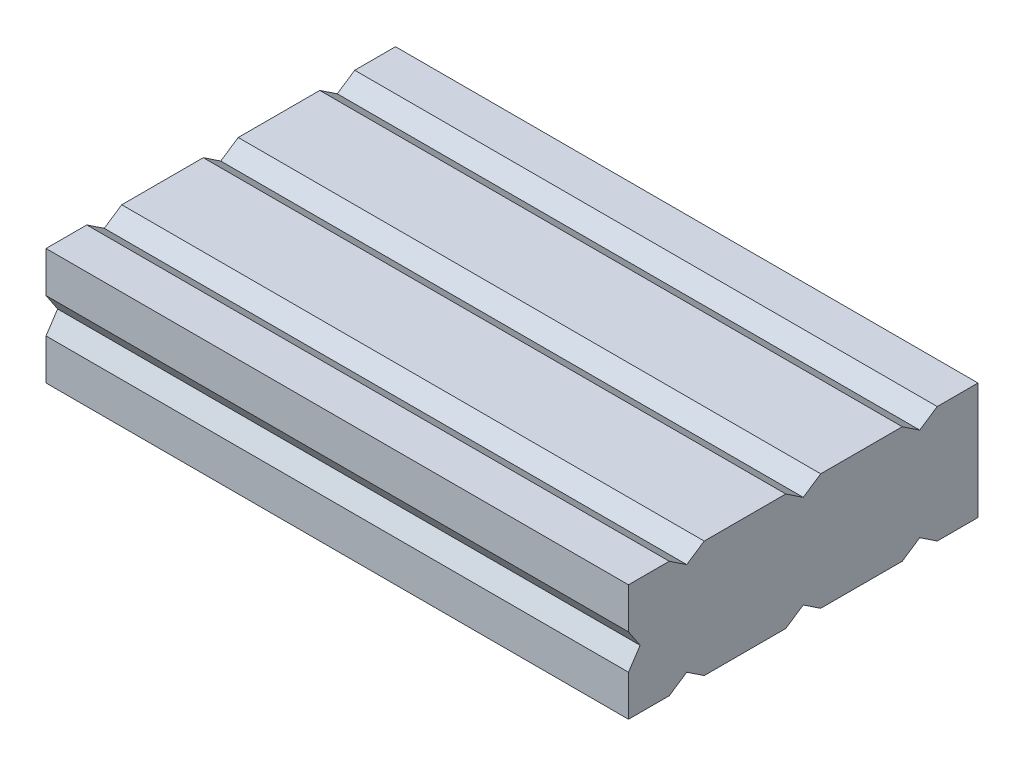
SolidWorks part; units mm, degrees
ref_plane "Front" through (0, 0, 0) normal (0, 0, 1) x (1, 0, 0)
ref_plane "Top" through (0, 0, 0) normal (0, 1, 0) x (1, 0, 0)
ref_plane "Right" through (0, 0, 0) normal (1, 0, 0) x (0, 0, -1)
sketch "Skizze1" plane through (0, 0, 0) normal (1, 0, 0) x (0, 0, -1)
  line L0 (-30, 10) -> (-30, -10) construction
  line L1 (-40, -10) -> (-33, -10)
  line L2 (-40, -10) -> (-40, -3)
  line L3 (-40, 10) -> (-33, 10)
  line L4 (40, -10) -> (40, -3)
  line L5 (-40, -10) -> (40, 10) construction
  line L6 (-40, 10) -> (40, -10) construction
  line L7 (-33, 10) -> (-30, 8)
  line L8 (-27, 10) -> (-30, 8)
  line L9 (0, 0) -> (-40, 0) construction
  line L10 (-7, 10) -> (-10, 8)
  line L11 (-13, 10) -> (-10, 8)
  line L12 (13, 10) -> (10, 8)
  line L13 (7, 10) -> (10, 8)
  line L14 (33, 10) -> (30, 8)
  line L15 (27, 10) -> (30, 8)
  line L16 (33, -10) -> (30, -8)
  line L17 (27, -10) -> (30, -8)
  line L18 (13, -10) -> (10, -8)
  line L19 (7, -10) -> (10, -8)
  line L20 (-7, -10) -> (-10, -8)
  line L21 (-13, -10) -> (-10, -8)
  line L22 (-33, -10) -> (-30, -8)
  line L23 (-27, -10) -> (-30, -8)
  line L24 (-40, 3) -> (-38, 0)
  line L25 (-40, -3) -> (-38, 0)
  line L26 (0, 0) -> (0, 10) construction
  line L27 (40, -3) -> (38, 0)
  line L28 (40, 3) -> (38, 0)
  line L29 (-30, 10) -> (-27, 10) construction
  line L30 (-27, 10) -> (-13, 10)
  line L31 (-33, 10) -> (-30, 10) construction
  line L32 (-40, 0) -> (-40, 3) construction
  line L33 (-40, 3) -> (-40, 10)
  line L34 (-40, -3) -> (-40, 0) construction
  line L35 (-33, -10) -> (-30, -10) construction
  line L36 (-27, -10) -> (-13, -10)
  line L37 (-30, -10) -> (-27, -10) construction
  line L38 (-13, -10) -> (-7, -10) construction
  line L39 (-7, -10) -> (7, -10)
  line L40 (7, -10) -> (13, -10) construction
  line L41 (13, -10) -> (27, -10)
  line L42 (-13, 10) -> (-7, 10) construction
  line L43 (-7, 10) -> (7, 10)
  line L44 (7, 10) -> (13, 10) construction
  line L45 (13, 10) -> (27, 10)
  line L46 (27, 10) -> (33, 10) construction
  line L47 (33, 10) -> (40, 10)
  line L48 (27, -10) -> (33, -10) construction
  line L49 (33, -10) -> (40, -10)
  line L50 (40, -3) -> (40, 3) construction
  line L51 (40, 3) -> (40, 10)
  line L52 (20, -10) -> (20, 10)
  point P0 (0, 0)
  dimension "D1" = 80
  dimension "D2" = 20
  dimension "D3" = 6
  dimension "D4" = 10
  dimension "D6" = 20
  dimension "D7" = 2
  dimension "D8" = 6
  dimension "D9" = 2
  dimension "D5" = 4
extrude "Aufsatz-Linear austragen1" add sketch "Skizze1" along normal blind 100 contours L41 L52 L45 L12 L13 L43 L10 L11 L30 L8 L7 L3 L33 L24 L25 L2 L1 L22 L23 L36 L21 L20 L39 L19 L18
